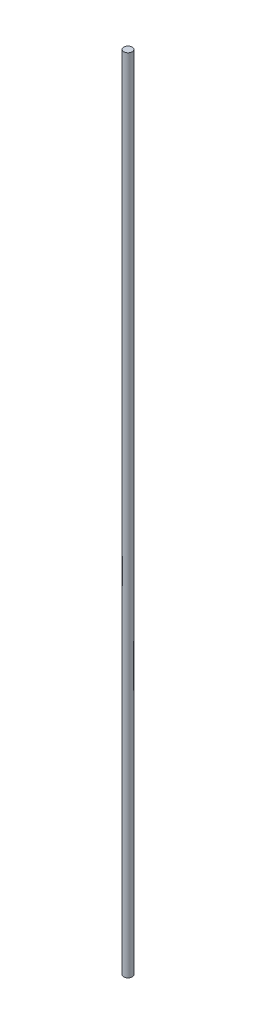
SolidWorks part; units mm, degrees
material "Plain Carbon Steel"
ref_plane "Front Plane" through (0, 0, 0) normal (0, 0, 1) x (1, 0, 0)
ref_plane "Top Plane" through (0, 0, 0) normal (0, 1, 0) x (1, 0, 0)
ref_plane "Right Plane" through (0, 0, 0) normal (1, 0, 0) x (0, 0, -1)
sketch "Sketch1" plane through (0, 0, 0) normal (0, 1, 0) x (1, 0, 0)
  circle A0 centre (0, 0) radius 4.7625
extrude "Boss-Extrude1" add sketch "Sketch1" along normal blind 914.4
